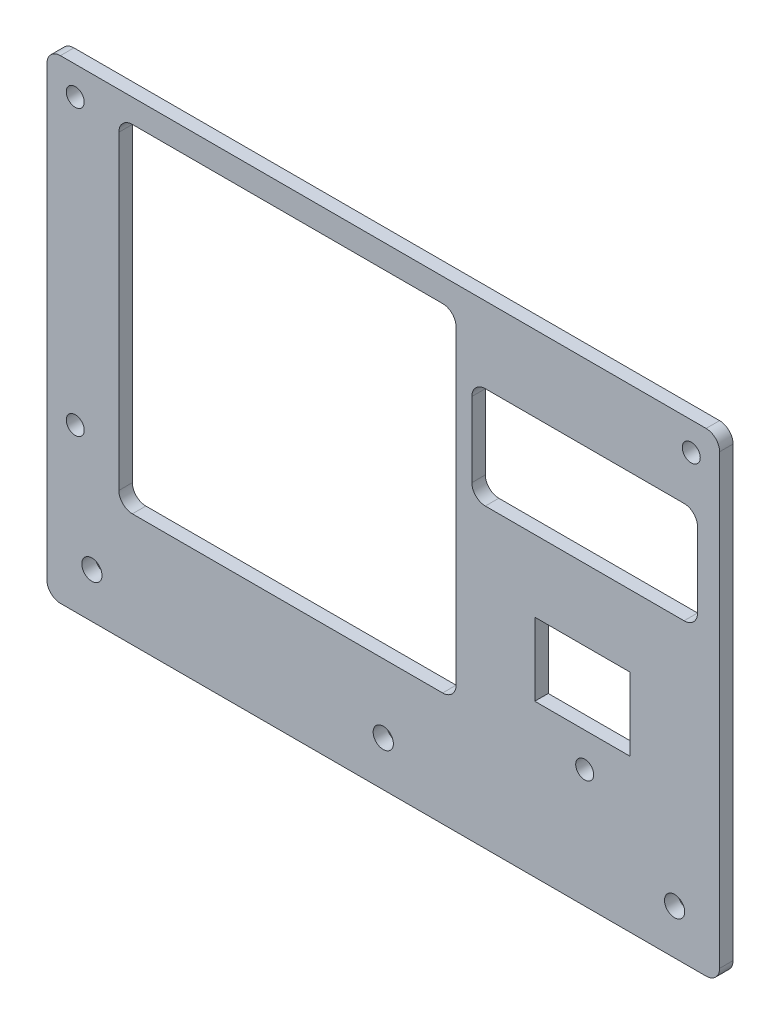
SolidWorks part; units mm, degrees
ref_plane "Płaszczyzna przednia" through (0, 0, 0) normal (0, 0, 1) x (1, 0, 0)
ref_plane "Płaszczyzna górna" through (0, 0, 0) normal (0, 1, 0) x (1, 0, 0)
ref_plane "Płaszczyzna prawa" through (0, 0, 0) normal (1, 0, 0) x (0, 0, -1)
sketch "Szkic1" plane through (0, 0, 0) normal (0, 0, 1) x (1, 0, 0)
  line L0 (-74.5132, 26.8296) -> (75.0868, 26.8296) construction
  line L1 (-74.5132, 69.5796) -> (75.0868, 69.5796)
  line L2 (-74.5132, 69.5796) -> (-74.5132, -15.9204)
  line L3 (-74.5132, -15.9204) -> (75.0868, -15.9204)
  line L4 (75.0868, 69.5796) -> (75.0868, -15.9204)
  line L5 (75.0868, -15.9204) -> (-74.5132, -15.9204)
  line L6 (75.0868, -15.9204) -> (75.0868, -35.9204)
  line L7 (75.0868, -35.9204) -> (-74.5132, -35.9204)
  line L8 (-74.5132, -15.9204) -> (-74.5132, -35.9204)
  line L9 (-58.5132, 64.3296) -> (16.4868, 64.3296)
  line L10 (-58.5132, 64.3296) -> (-58.5132, -10.6704)
  line L11 (-58.5132, -10.6704) -> (16.4868, -10.6704)
  line L12 (16.4868, 64.3296) -> (16.4868, -10.6704)
  line L13 (19.9868, 52.6796) -> (70.1868, 52.6796)
  line L14 (19.9868, 52.6796) -> (19.9868, 30.0796)
  line L15 (19.9868, 30.0796) -> (70.1868, 30.0796)
  line L16 (70.1868, 52.6796) -> (70.1868, 30.0796)
  line L17 (33.9868, 14.1796) -> (55.1868, 14.1796)
  line L18 (33.9868, 14.1796) -> (33.9868, -2.0204)
  line L19 (33.9868, -2.0204) -> (55.1868, -2.0204)
  line L20 (55.1868, 14.1796) -> (55.1868, -2.0204)
  line L21 (-74.5132, -25.9204) -> (75.0868, -25.9204) construction
  circle A0 centre (-68.2132, 63.2796) radius 2
  circle A1 centre (-68.2132, 0.0796) radius 2
  circle A2 centre (68.7868, 63.2796) radius 2
  circle A3 centre (45.0868, -9.6204) radius 2
  circle A4 centre (-64.5132, -25.9204) radius 2.25
  circle A5 centre (0.2868, -25.9204) radius 2.25
  circle A6 centre (65.0868, -25.9204) radius 2.25
  dimension "D20" = 4.5
  dimension "D21" = 4.5
  dimension "D22" = 4.5
  dimension "D23" = 10
  dimension "D29" = 4
  dimension "D1" = 85.5
  dimension "D2" = 149.6
  dimension "D3" = 20
  dimension "D4" = 75
  dimension "D5" = 75
  dimension "D6" = 50.2
  dimension "D7" = 21.2
  dimension "D8" = 22.6
  dimension "D9" = 16.2
  dimension "D10" = 16
  dimension "D11" = 37.5
  dimension "D12" = 30
  dimension "D13" = 6.3
  dimension "D14" = 6.3
  dimension "D15" = 6.3
  dimension "D16" = 6.3
  dimension "D17" = 6.3
  dimension "D18" = 6.3
  dimension "D19" = 16
  dimension "D24" = 10
  dimension "D25" = 19.9
  dimension "D26" = 13.9
  dimension "D27" = 16.9
  dimension "D28" = 4.9
extrude "Dodanie-wyciągnięcie1" add sketch "Szkic1" along normal blind 3 contours L4 L1 L2 L3 A3 A2 A1 A0 L9 L12 L11 L10 L13 L16 L15 L14 L17 L20 L19 L18 | L3 L8 L7 L6 A6 A5 A4
fillet "Zaokrąglenie1" radius 3 8 edges at (16.4868, -10.6704, 1.5) (16.4868, 64.3296, 1.5) (-58.5132, 64.3296, 1.5) (-58.5132, -10.6704, 1.5) (75.0868, -35.9204, 1.5) (-74.5132, -35.9204, 1.5) (75.0868, 69.5796, 1.5) (-74.5132, 69.5796, 1.5)
fillet "Zaokrąglenie2" radius 3 4 edges at (70.1868, 30.0796, 1.5) (19.9868, 30.0796, 1.5) (70.1868, 52.6796, 1.5) (19.9868, 52.6796, 1.5)
